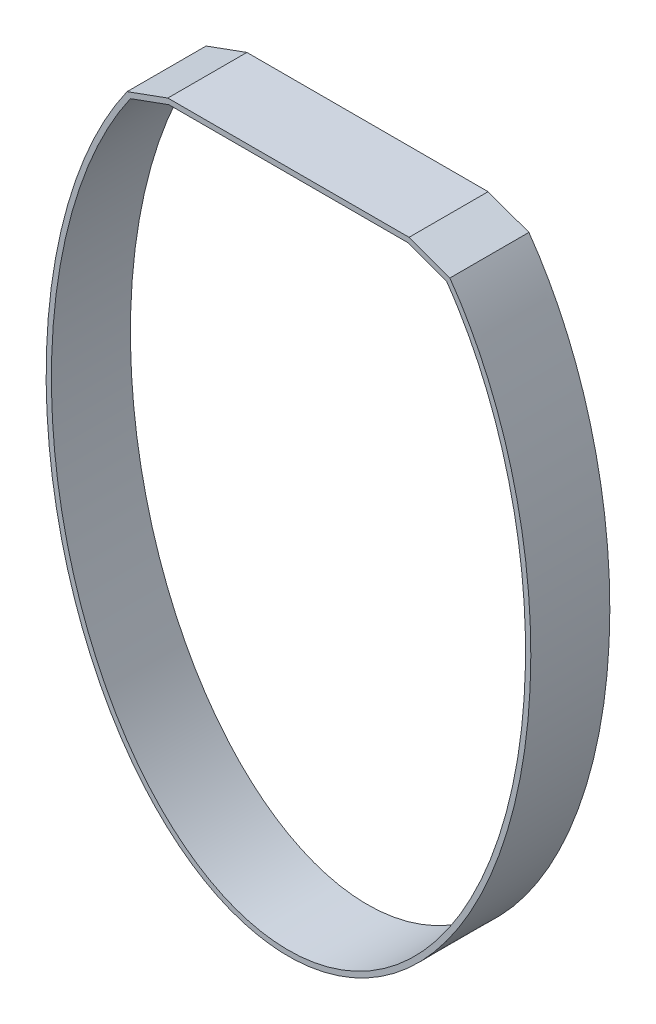
SolidWorks part; units mm, degrees
material "ABS"
ref_plane "Front Plane" through (0, 0, 0) normal (0, 0, 1) x (1, 0, 0)
ref_plane "Top Plane" through (0, 0, 0) normal (0, 1, 0) x (1, 0, 0)
ref_plane "Right Plane" through (0, 0, 0) normal (1, 0, 0) x (0, 0, -1)
sketch "Sketch1" plane through (0, 0, 0) normal (0, 0, 1) x (1, 0, 0)
  line L0 (-60, -5.3021) -> (60, -5.3021) construction
  line L1 (-45.4326, 0) -> (45.4326, 0)
  line L2 (-45.4326, 0) -> (-60, -5.3021)
  line L3 (45.4326, 0) -> (60, -5.3021)
  line L4 (0, -112.0648) -> (0, 0) construction
  line L5 (45.7853, 2) -> (61.2724, -3.6369)
  line L6 (-45.7853, 2) -> (45.7853, 2)
  line L7 (-45.7853, 2) -> (-61.2724, -3.6369)
  ellipse E0 centre (0, -112.0648) end of major axis (0, 31.1724) minor radius 90 (-60, -5.3021) -> (60, -5.3021) ccw
  spline S0 degree 1 poles (-61.2724, -3.6369) (61.2724, -3.6369) knots 0 0 1 1 construction
  spline S1 degree 3 poles (-61.2724, -3.6369) (-62.1418, -4.8612) (-63.8269, -7.3269) (-67.0999, -12.49) (-70.9445, -19.286) (-75.1566, -27.9673) (-80.2018, -40.1697) (-85.3891, -56.4755) (-89.6881, -77.2885) (-91.9684, -98.8809) (-92.2545, -128.0656) (-87.4126, -164.054) (-73.765, -202.6056) (-53.4466, -233.085) (-28.1439, -252.7405) (0, -259.5829) (28.1439, -252.7405) (53.4466, -233.085) (73.765, -202.6056) (87.4126, -164.054) (92.2545, -128.0656) (91.9684, -98.8809) (89.6881, -77.2885) (85.3891, -56.4755) (80.2018, -40.1697) (75.1566, -27.9673) (70.9445, -19.286) (67.0999, -12.49) (63.8269, -7.3269) (62.1418, -4.8612) (61.2724, -3.6369) knots 0.724399 0.724399 0.724399 0.724399 0.762168 0.799936 0.875474 0.951011 1.026548 1.177623 1.328697 1.479772 1.630847 1.932996 2.235145 2.537294 2.839443 3.141593 3.443742 3.745891 4.04804 4.350189 4.652339 4.803413 4.954488 5.105562 5.256637 5.332174 5.407712 5.483249 5.521018 5.558786 5.558786 5.558786 5.558786
  point P2 (0, -5.3021)
  point P5 (33.6815, -227.9183)
  point P6 (0, 0)
  point P10 (0, -241.0168)
  point P15 (0.0312, -588.6056)
  point P16 (-87.1205, -110.2604)
  point P17 (0, 0)
  dimension "D1" = 120
  dimension "D2" = 14.5674
  dimension "D3" = 5.3021
  dimension "D4" = 250
  dimension "D5" = 180
  dimension "D6" = 2
extrude "Boss-Extrude1" add sketch "Sketch1" along normal mid plane 30
